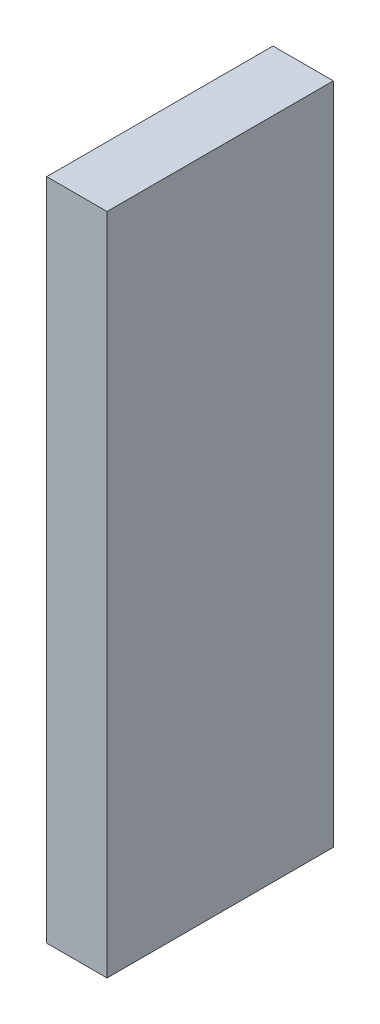
SolidWorks part; units mm, degrees
ref_plane "前视基准面" through (0, 0, 0) normal (0, 0, 1) x (1, 0, 0)
ref_plane "上视基准面" through (0, 0, 0) normal (0, 1, 0) x (1, 0, 0)
ref_plane "右视基准面" through (0, 0, 0) normal (1, 0, 0) x (0, 0, -1)
other "Configuration Table"
sketch "草图1" plane through (0, 0, 0) normal (0, 0, 1) x (1, 0, 0)
  line L0 (0, 0) -> (4, 0)
  line L1 (4, 0) -> (4, 44)
  line L2 (4, 44) -> (0, 44)
  line L3 (0, 44) -> (0, 0)
  dimension "width" = 4
  dimension "height" = 44
extrude "Mount_spacer" add sketch "草图1" along normal blind 15
